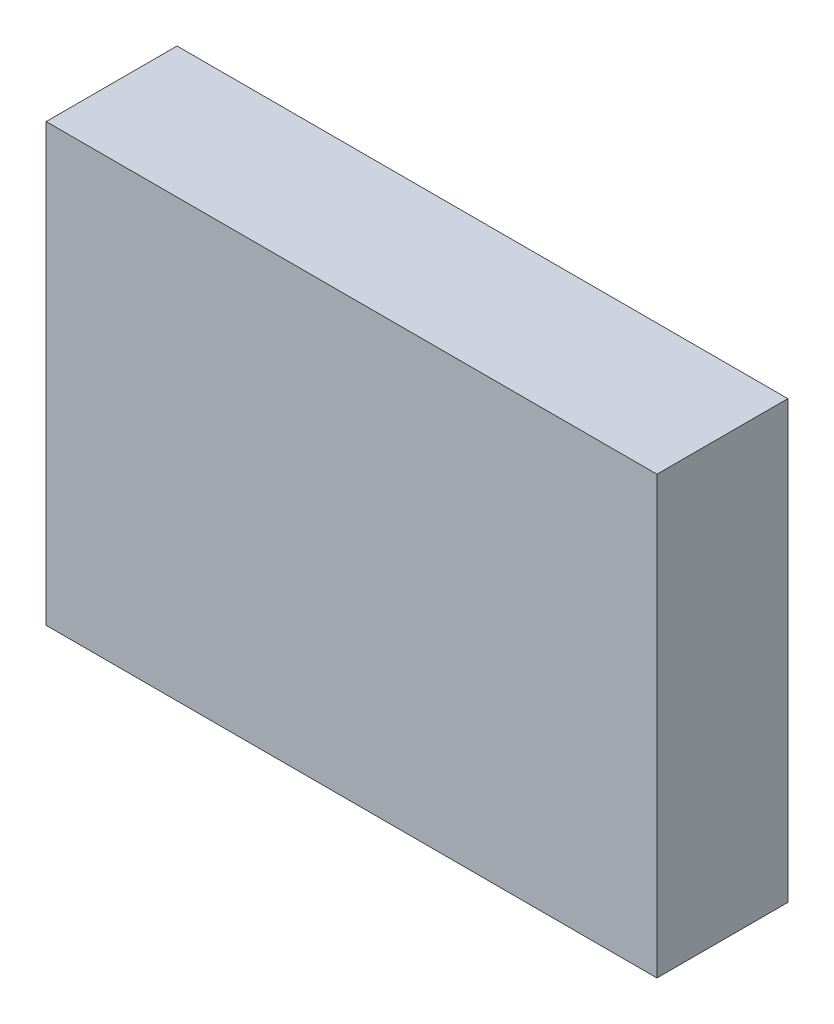
SolidWorks part; units mm, degrees
material "Pine"
ref_plane "Front Plane" through (0, 0, 0) normal (0, 0, 1) x (1, 0, 0)
ref_plane "Top Plane" through (0, 0, 0) normal (0, 1, 0) x (1, 0, 0)
ref_plane "Right Plane" through (0, 0, 0) normal (1, 0, 0) x (0, 0, -1)
sketch "Sketch1" plane through (0, 0, 0) normal (0, 0, 1) x (1, 0, 0)
  line L1 (-49.3568, 43.9839) -> (39.5432, 43.9839)
  line L2 (-49.3568, 43.9839) -> (-49.3568, -19.5161)
  line L3 (-49.3568, -19.5161) -> (39.5432, -19.5161)
  line L4 (39.5432, 43.9839) -> (39.5432, -19.5161)
extrude "Boss-Extrude1" add sketch "Sketch1" along normal blind 19.05
